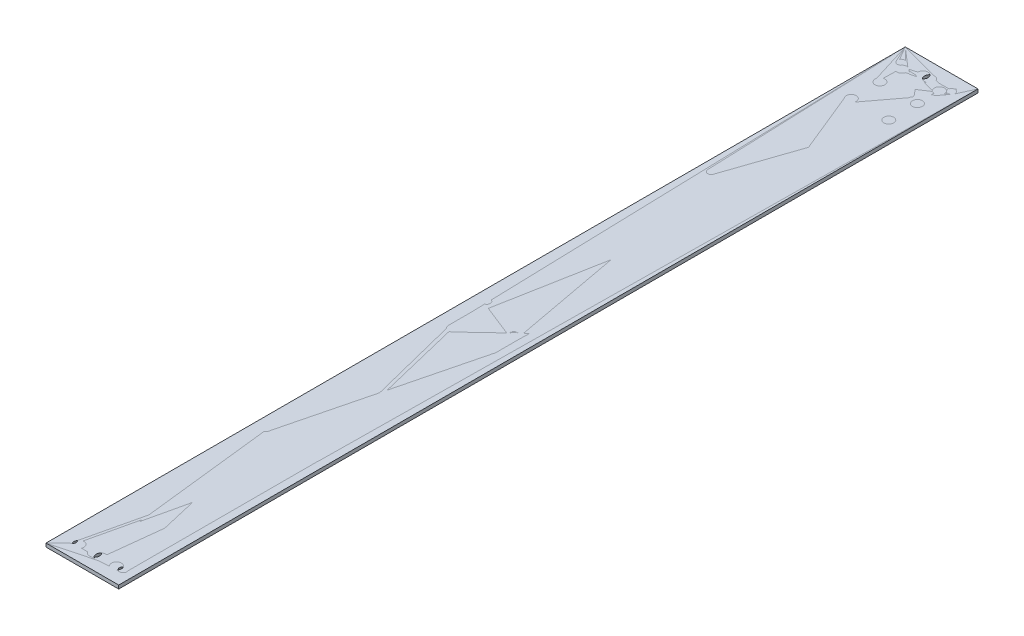
SolidWorks part; units mm, degrees
ref_plane "Front Plane" through (0, 0, 0) normal (0, 0, 1) x (1, 0, 0)
ref_plane "Top Plane" through (0, 0, 0) normal (0, 1, 0) x (1, 0, 0)
ref_plane "Right Plane" through (0, 0, 0) normal (1, 0, 0) x (0, 0, -1)
sketch "Sketch1" plane through (0, 0, 0) normal (0, 1, 0) x (1, 0, 0)
  line L1 (-16.5, -195) -> (16.5, -195)
  line L2 (-16.5, -195) -> (-16.5, 195)
  line L3 (-16.5, 195) -> (16.5, 195)
  line L4 (16.5, -195) -> (16.5, 195)
  line L5 (-16.5, -195) -> (16.5, 195) construction
  line L6 (-16.5, 195) -> (16.5, -195) construction
  point P0 (0, 0)
  dimension "D1" = 33
  dimension "D2" = 390
extrude "Boss-Extrude1" add sketch "Sketch1" along normal blind 1.5875
hole_wizard "M4 Clearance Hole1" positions "Sketch4" profile "Sketch5" hole size "M4" standard "ANSI Metric" end condition through all
sketch "Sketch4" plane through (0, 1.5875, 0) normal (0, 1, 0) x (1, 0, 0)
  line L4 (16.5, -195) -> (16.5, 195) construction
  line L5 (16.5, 195) -> (-16.5, 195) construction
  line L6 (-8.5, 185.5) -> (-8.5, 175.5)
  line L8 (-16.5, 195) -> (-16.5, -195) construction
  line L9 (-8.5, 162.5) -> (-8.5, -7.5)
  line L11 (-8.5, -18) -> (-8.5, -188)
  line L12 (-16.5, -195) -> (16.5, -195) construction
  line L13 (-0.8731, 0) -> (0.8731, 0) construction
  point P9 (1.5, 188)
  point P16 (-8.5, 185.5)
  point P17 (-8.5, 175.5)
  point P27 (-8.5, 162.5)
  point P28 (-8.5, -7.5)
  point P32 (-8.5, -18)
  point P33 (-8.5, -188)
  point P52 (1.5, -188)
  dimension "D1" = 15
  dimension "D2" = 7
  dimension "D3" = 10
  dimension "D4" = 9.5
  dimension "D5" = 8
  dimension "D6" = 170
  dimension "D7" = 13
  dimension "D8" = 10.5
  dimension "D9" = 170
  dimension "D10" = 7
sketch "Sketch5" plane through (1.5, 1.5875, -188) normal (1, 0, 0) x (0, 0, 1)
  line L0 (0, 0) -> (0, 1.5875)
  line L1 (0, 1.5875) -> (2.25, 1.5875)
  line L2 (2.25, 1.5875) -> (2.25, 0)
  line L5 (2.25, 0) -> (0, 0)
  line L11 (0, -6.35) -> (0, 107.95) construction
  dimension "Thru Hole Dia." = 4.5
  dimension "Thru Hole Depth" = 1.5875
hole_wizard "M4x0.7 Tapped Hole1" positions "Sketch6" profile "Sketch8" tap size "M4x0.7" standard "ANSI Metric" end condition through all
sketch "Sketch6" plane through (0, 1.5875, 0) normal (0, 1, 0) x (1, 0, 0)
  line L0 (16.5, -195) -> (16.5, 195) construction
  line L1 (16.5, 195) -> (-16.5, 195) construction
  line L2 (-0.8731, 0) -> (0.8731, 0) construction
  line L3 (11.5, 100) -> (11.5, -100)
  line L4 (11.5, 102) -> (11.5, 112)
  point P0 (11.5, 188)
  point P9 (11.5, -188)
  point P12 (11.5, -100)
  point P20 (11.5, 0)
  point P23 (11.5, 102)
  point P24 (11.5, 112)
  point P29 (11.5, 107)
  dimension "D1" = 5
  dimension "D2" = 7
  dimension "D3" = 200
  dimension "D4" = 5
  dimension "D5" = 10
  dimension "D6" = 81
sketch "Sketch8" plane through (11.5, 1.5875, -188) normal (1, 0, 0) x (0, 0, 1)
  line L0 (0, 0) -> (0, 1.5875)
  line L1 (0, 1.5875) -> (1.65, 1.5875)
  line L2 (1.65, 1.5875) -> (1.65, 0)
  line L5 (1.65, 0) -> (0, 0)
  line L11 (0, -6.35) -> (0, 107.95) construction
  dimension "Thru Tap Drill Dia." = 3.3
  dimension "Thru Tap Drill Depth" = 1.5875
cosmetic thread "Hole Thread1" parameters "D2"=4
cosmetic thread "Hole Thread2" parameters "D2"=4
cosmetic thread "Hole Thread3" parameters "D2"=4
cosmetic thread "Hole Thread4" parameters "D2"=4
cosmetic thread "Hole Thread11" parameters "D2"=4
cosmetic thread "Hole Thread12" parameters "D2"=4
mirror "Mirror1" about plane through (0, 0, 0) normal (1, 0, 0) of bodies 103
cosmetic thread "Hole Thread6" parameters "D2"=4
cosmetic thread "Hole Thread7" parameters "D2"=4
cosmetic thread "Hole Thread9" parameters "D2"=4
cosmetic thread "Hole Thread10" parameters "D2"=4
cosmetic thread "Hole Thread13" parameters "D2"=4
cosmetic thread "Hole Thread14" parameters "D2"=4
